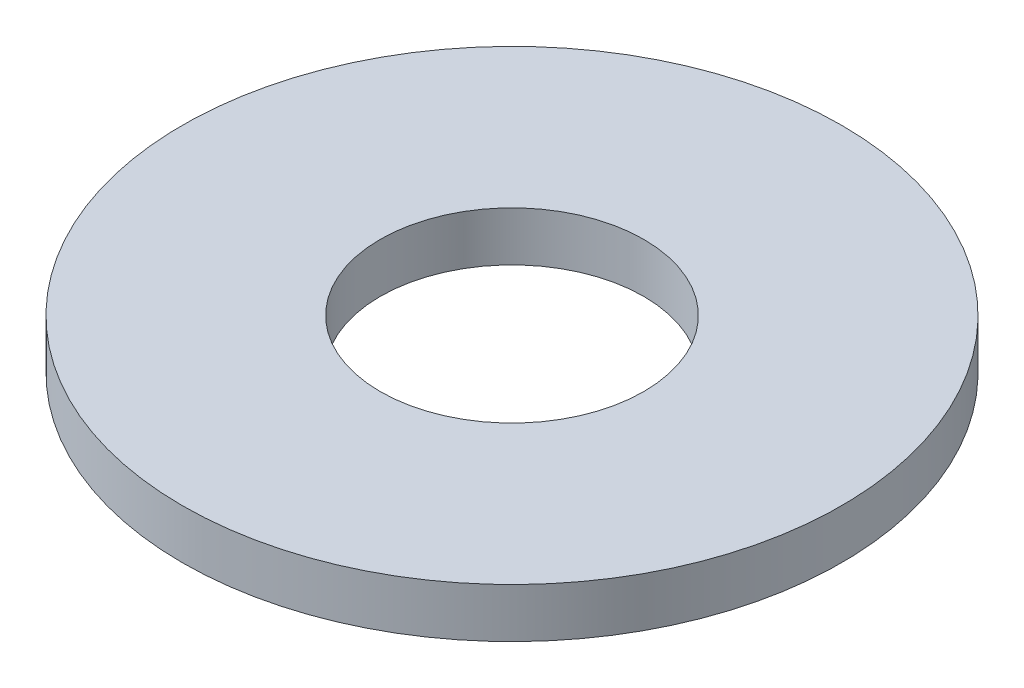
SolidWorks part; units mm, degrees
ref_plane "Alzado" through (0, 0, 0) normal (0, 0, 1) x (1, 0, 0)
ref_plane "Planta" through (0, 0, 0) normal (0, 1, 0) x (1, 0, 0)
ref_plane "Vista lateral" through (0, 0, 0) normal (1, 0, 0) x (0, 0, -1)
sketch "Sketch1" plane through (0, 0, 0) normal (0, 1, 0) x (1, 0, 0)
  circle A0 centre (0, 0) radius 5
  circle A1 centre (0, 0) radius 2
  dimension "D1" = 10
  dimension "D2" = 4
extrude "Boss-Extrude1" add sketch "Sketch1" along normal blind 0.75
